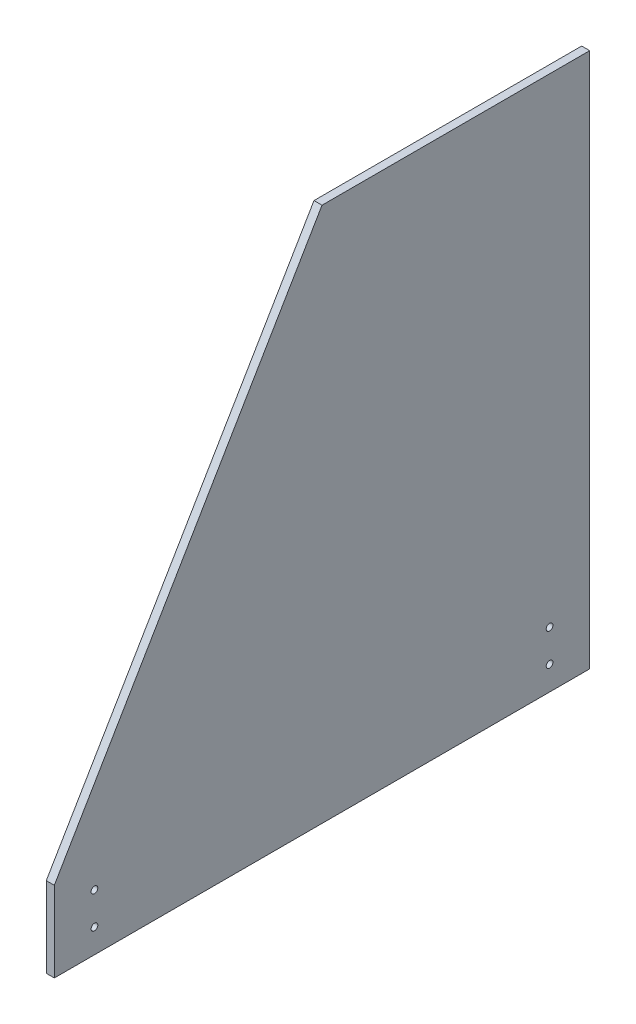
SolidWorks part; units mm, degrees
ref_plane "Front Plane" through (0, 0, 0) normal (0, 0, 1) x (1, 0, 0)
ref_plane "Top Plane" through (0, 0, 0) normal (0, 1, 0) x (1, 0, 0)
ref_plane "Right Plane" through (0, 0, 0) normal (1, 0, 0) x (0, 0, -1)
sketch "Sketch1" plane through (0, 0, 0) normal (1, 0, 0) x (0, 0, -1)
  line L0 (0, -2343.7616) -> (0, 114844.3172) construction
  line L1 (-2343.7616, 0) -> (114844.3172, 0) construction
  line L2 (0, 60) -> (400, 60) construction
  line L3 (0, 0) -> (400, 0)
  line L5 (200, 400) -> (400, 400)
  line L6 (400, 0) -> (400, 400)
  line L7 (0, 60) -> (200, 400)
  line L8 (0, 60) -> (0, 0)
  line L9 (-1000, 30) -> (49000, 30) construction
  line L10 (200, -1000) -> (200, 49000) construction
  circle A0 centre (30, 42) radius 2.5
  circle A2 centre (30, 18) radius 2.5
  circle A3 centre (370, 18) radius 2.5
  circle A4 centre (370, 42) radius 2.5
  point P14 (0, 30)
  point P21 (200, 0)
  dimension "D7" = 5
  dimension "D1" = 400
  dimension "D2" = 400
  dimension "D3" = 60
  dimension "D4" = 200
  dimension "D5" = 30
  dimension "D8" = 12
extrude "Boss-Extrude1" add sketch "Sketch1" along normal blind 6
